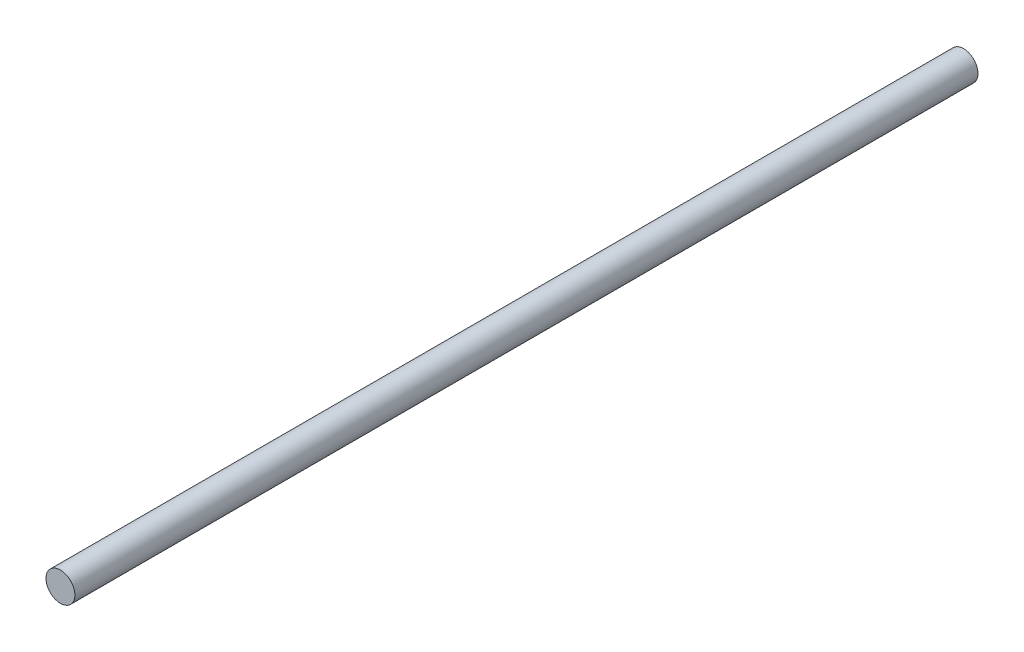
SolidWorks part; units mm, degrees
material "Plain Carbon Steel"
ref_plane "Front Plane" through (0, 0, 0) normal (0, 0, 1) x (1, 0, 0)
ref_plane "Top Plane" through (0, 0, 0) normal (0, 1, 0) x (1, 0, 0)
ref_plane "Right Plane" through (0, 0, 0) normal (1, 0, 0) x (0, 0, -1)
sketch "Sketch1" plane through (0, 0, 0) normal (0, 0, 1) x (1, 0, 0)
  circle A0 centre (0, 0) radius 10.16
  dimension "D1" = 20.32
extrude "Boss-Extrude1" add sketch "Sketch1" against normal blind 635
